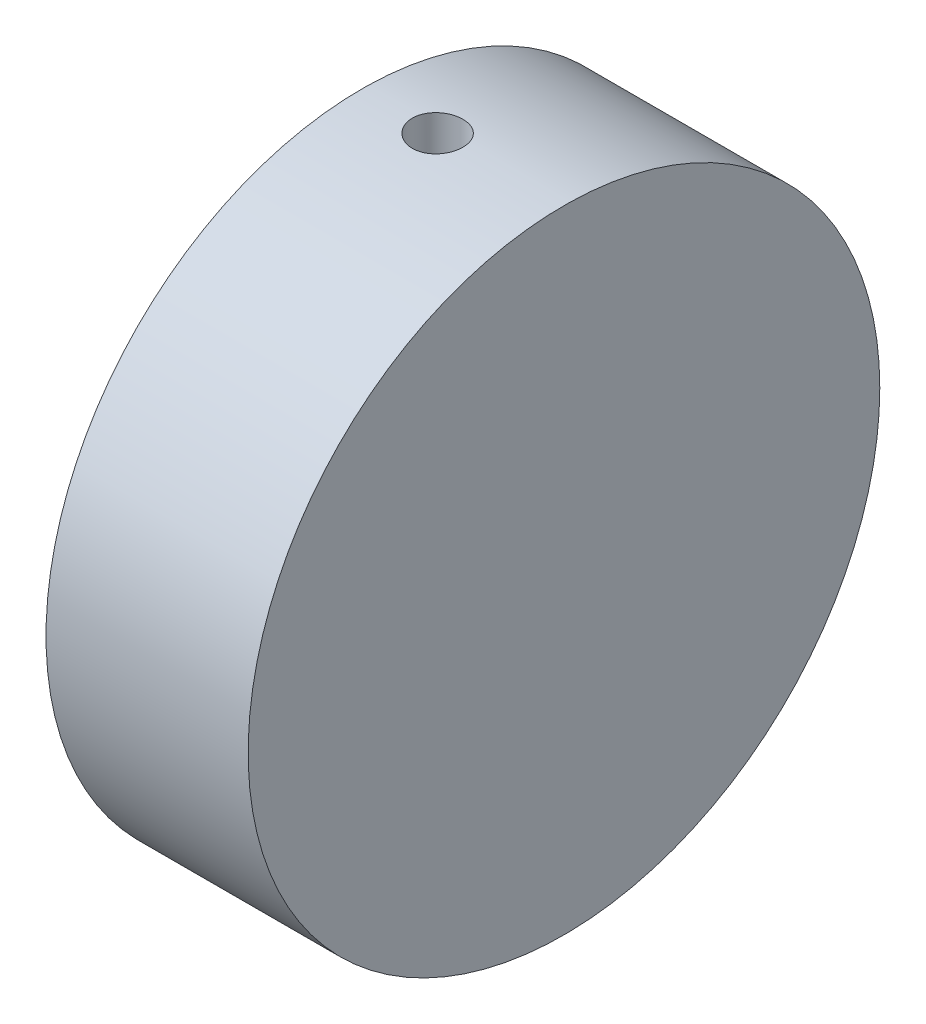
SolidWorks part; units mm, degrees
ref_plane "前视基准面" through (0, 0, 0) normal (0, 0, 1) x (1, 0, 0)
ref_plane "上视基准面" through (0, 0, 0) normal (0, 1, 0) x (1, 0, 0)
ref_plane "右视基准面" through (0, 0, 0) normal (1, 0, 0) x (0, 0, -1)
other "Configuration Table"
sketch "草图1" plane through (0, 0, 0) normal (1, 0, 0) x (0, 0, -1)
  circle A0 centre (0, 0) radius 12.5
  dimension "D1" = 25
extrude "凸台-拉伸1" add sketch "草图1" along normal blind 8
sketch "草图2" plane through (0, 0, 0) normal (-1, 0, 0) x (0, 0, 1)
  circle A0 centre (0, 0) radius 3.2
  dimension "D1" = 6.4
extrude "切除-拉伸1" cut sketch "草图2" against normal blind 6
sketch "草图3" plane through (0, 0, 0) normal (0, 1, 0) x (1, 0, 0)
  line L0 (0, 12.5) -> (0, -12.5) construction
  circle A0 centre (3, 0) radius 1
  dimension "D1" = 2
  dimension "D2" = 3
extrude "切除-拉伸2" cut sketch "草图3" against normal up to next and the other way up to next
